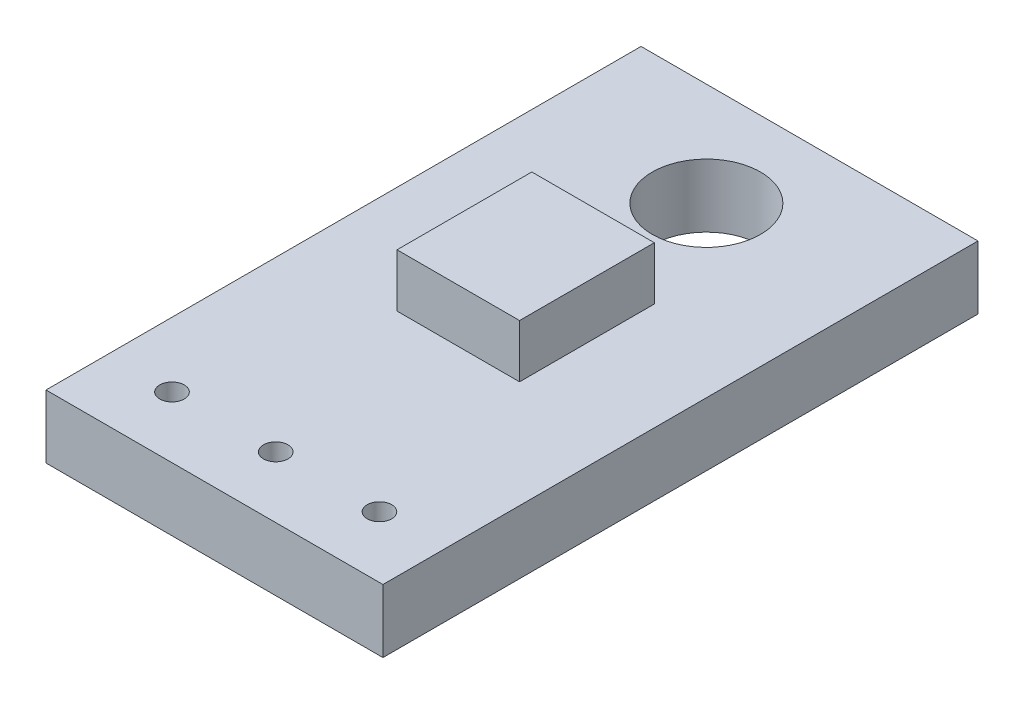
SolidWorks part; units mm, degrees
ref_plane "Front Plane" through (0, 0, 0) normal (0, 0, 1) x (1, 0, 0)
ref_plane "Top Plane" through (0, 0, 0) normal (0, 1, 0) x (1, 0, 0)
ref_plane "Right Plane" through (0, 0, 0) normal (1, 0, 0) x (0, 0, -1)
sketch "Sketch1" plane through (0, 0, 0) normal (0, 1, 0) x (1, 0, 0)
  line L1 (0, 0) -> (8.25, 0)
  line L2 (0, 0) -> (0, 14.57)
  line L3 (0, 14.57) -> (8.25, 14.57)
  line L4 (8.25, 0) -> (8.25, 14.57)
  dimension "D1" = 8.25
  dimension "D2" = 14.57
extrude "Boss-Extrude1" add sketch "Sketch1" along normal blind 1.55
sketch "Sketch2" plane through (0, 1.55, 0) normal (0, 1, 0) x (1, 0, 0)
  line L0 (4.125, 14.57) -> (4.125, 0) construction
  line L1 (8.25, 14.57) -> (0, 14.57) construction
  line L2 (0, 0) -> (8.25, 0) construction
  circle A0 centre (4.125, 12.045) radius 1.325
  dimension "D1" = 2.65
  dimension "D2" = 1.2
extrude "Cut-Extrude1" cut sketch "Sketch2" against normal through all
sketch "Sketch3" plane through (0, 1.55, 0) normal (0, 1, 0) x (1, 0, 0)
  line L0 (4.125, 14.57) -> (4.125, 0) construction
  line L1 (2.625, 9.27) -> (5.625, 9.27)
  line L2 (2.625, 9.27) -> (2.625, 5.97)
  line L3 (2.625, 5.97) -> (5.625, 5.97)
  line L4 (5.625, 9.27) -> (5.625, 5.97)
  line L5 (8.25, 14.57) -> (0, 14.57) construction
  line L6 (0, 0) -> (8.25, 0) construction
  dimension "D1" = 3
  dimension "D2" = 3.3
  dimension "D3" = 5.3
extrude "Boss-Extrude2" add sketch "Sketch3" along normal blind 1.3
hole_wizard "Ø0.6 (0.6) Diameter Hole1" positions "Sketch5" profile "Sketch4" hole size "Ø0.6" standard "ANSI Metric"
sketch "Sketch5" plane through (0, 1.55, 0) normal (0, 1, 0) x (1, 0, 0)
  line L0 (0, 1.5) -> (8.25, 1.5) construction
  line L1 (0, 14.57) -> (0, 0) construction
  line L2 (8.25, 0) -> (8.25, 14.57) construction
  line L3 (0, 0) -> (8.25, 0) construction
  point P8 (4.125, 1.5)
  point P12 (1.585, 1.5)
  point P14 (6.665, 1.5)
  dimension "D1" = 2.54
  dimension "D2" = 2.54
  dimension "D3" = 1.5
sketch "Sketch4" plane through (4.125, 1.55, -1.5) normal (1, 0, 0) x (0, 0, 1)
  line L0 (0, 0) -> (0, 2.1803)
  line L1 (0, 2.1803) -> (0.3, 2)
  line L2 (0.3, 2) -> (0.3, 0)
  line L5 (0.3, 0) -> (0, 0)
  line L10 (0, 2.1803) -> (-0.3, 2) construction
  line L11 (0, -6.35) -> (0, 107.95) construction
  dimension "Hole Dia." = 0.6
  dimension "Hole Depth" = 2
  dimension "Drill Angle" = 118
